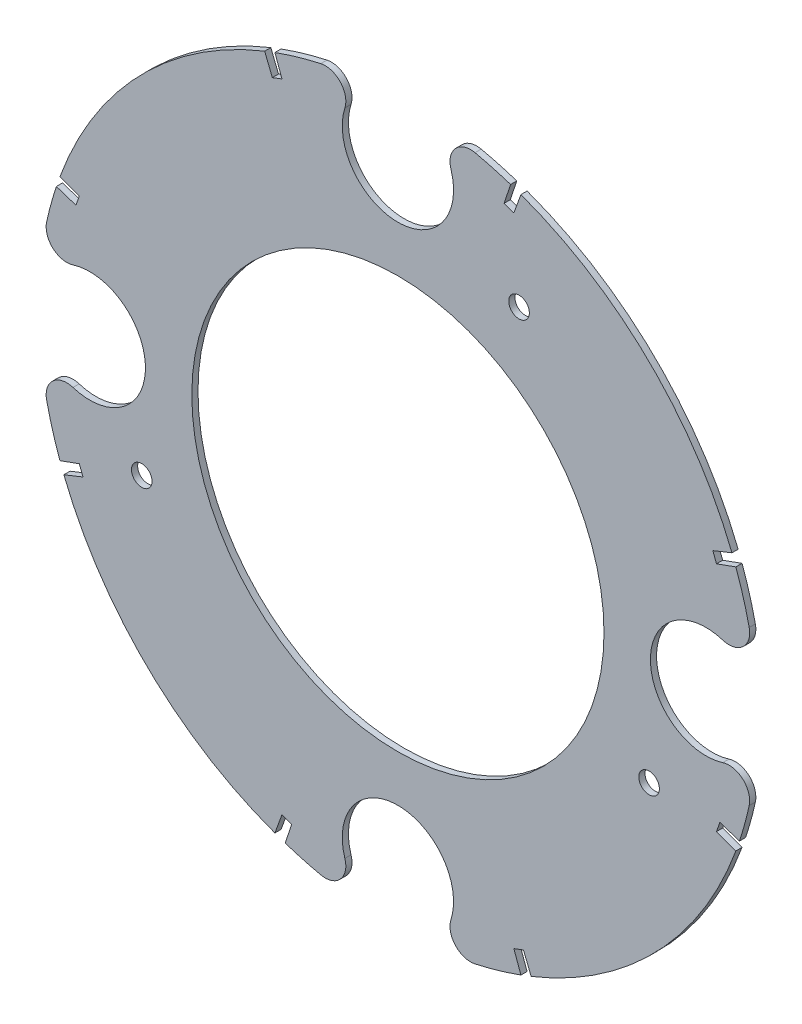
SolidWorks part; units mm, degrees
ref_plane "Front Plane" through (0, 0, 0) normal (0, 0, 1) x (1, 0, 0)
ref_plane "Top Plane" through (0, 0, 0) normal (0, 1, 0) x (1, 0, 0)
ref_plane "Right Plane" through (0, 0, 0) normal (1, 0, 0) x (0, 0, -1)
sketch "Sketch1" plane through (0, 0, 0) normal (0, 0, 1) x (1, 0, 0)
  line L0 (-174.5, 0) -> (-72.12, 0) construction
  line L1 (0, 0) -> (0, -168.1678) construction
  line L14 (-56.2623, -154.5794) -> (-51.5384, -156.2179)
  line L15 (72.12, 0) -> (174.5, 0) construction
  line L16 (-54.6714, -165.7145) -> (-51.5384, -156.2179)
  line L17 (-59.6825, -163.9764) -> (-56.2623, -154.5794)
  line L18 (59.6825, -163.9764) -> (56.2623, -154.5794)
  line L19 (64.6385, -162.0868) -> (60.9342, -152.7981)
  line L20 (56.2623, -154.5794) -> (60.9342, -152.7981)
  line L21 (-163.9764, 59.6825) -> (-154.5794, 56.2623)
  line L22 (-154.5794, 56.2623) -> (-156.2179, 51.5384)
  line L23 (-165.7145, 54.6714) -> (-156.2179, 51.5384)
  line L24 (-163.9764, -59.6825) -> (-154.5794, -56.2623)
  line L25 (-154.5794, -56.2623) -> (-152.7981, -60.9342)
  line L26 (-162.0868, -64.6385) -> (-152.7981, -60.9342)
  line L27 (59.6825, 163.9764) -> (56.2623, 154.5794)
  line L28 (56.2623, 154.5794) -> (51.5384, 156.2179)
  line L29 (54.6714, 165.7145) -> (51.5384, 156.2179)
  line L30 (-59.6825, 163.9764) -> (-56.2623, 154.5794)
  line L31 (-56.2623, 154.5794) -> (-60.9342, 152.7981)
  line L32 (-64.6385, 162.0868) -> (-60.9342, 152.7981)
  line L33 (163.9764, -59.6825) -> (154.5794, -56.2623)
  line L34 (154.5794, -56.2623) -> (156.2179, -51.5384)
  line L35 (165.7145, -54.6714) -> (156.2179, -51.5384)
  line L36 (163.9764, 59.6825) -> (154.5794, 56.2623)
  line L37 (154.5794, 56.2623) -> (152.7981, 60.9342)
  line L38 (162.0868, 64.6385) -> (152.7981, 60.9342)
  arc A5 (-157.6539, -25.7393) -> (-157.6539, 25.7393) centre (-149.5, 0) ccw
  arc A6 (-170.4413, 37.4166) -> (-157.6539, 25.7393) centre (-160.6739, 35.2724) ccw
  arc A7 (-170.4413, -37.4166) -> (-157.6539, -25.7393) centre (-160.6739, -35.2724) cw
  arc A8 (37.4166, 170.4413) -> (25.7393, 157.6539) centre (35.2724, 160.6739) ccw
  arc A9 (-25.7393, 157.6539) -> (25.7393, 157.6539) centre (0, 149.5) ccw
  arc A10 (-37.4166, 170.4413) -> (-25.7393, 157.6539) centre (-35.2724, 160.6739) cw
  arc A11 (170.4413, -37.4166) -> (157.6539, -25.7393) centre (160.6739, -35.2724) ccw
  arc A12 (157.6539, 25.7393) -> (157.6539, -25.7393) centre (149.5, 0) ccw
  arc A13 (170.4413, 37.4166) -> (157.6539, 25.7393) centre (160.6739, 35.2724) cw
  arc A14 (-37.4166, -170.4413) -> (-25.7393, -157.6539) centre (-35.2724, -160.6739) ccw
  arc A15 (25.7393, -157.6539) -> (-25.7393, -157.6539) centre (0, -149.5) ccw
  arc A16 (37.4166, -170.4413) -> (25.7393, -157.6539) centre (35.2724, -160.6739) cw
  circle A30 centre (121.8734, -52.131) radius 5
  circle A31 centre (58.7754, 116.258) radius 5
  circle A32 centre (-124.2895, -46.0393) radius 5
  circle A41 centre (0, 0) radius 100
  arc A42 (-54.6714, -165.7145) -> (-37.4166, -170.4413) centre (0, 0) ccw
  arc A43 (64.6385, -162.0868) -> (163.9764, -59.6825) centre (0, 0) ccw
  arc A44 (-162.0868, -64.6385) -> (-59.6825, -163.9764) centre (0, 0) ccw
  arc A45 (-170.4413, -37.4166) -> (-163.9764, -59.6825) centre (0, 0) ccw
  arc A46 (-37.4166, 170.4413) -> (-59.6825, 163.9764) centre (0, 0) ccw
  arc A47 (170.4413, 37.4166) -> (163.9764, 59.6825) centre (0, 0) ccw
  arc A48 (37.4166, -170.4413) -> (59.6825, -163.9764) centre (0, 0) ccw
  arc A49 (-165.7145, 54.6714) -> (-170.4413, 37.4166) centre (0, 0) ccw
  arc A50 (-64.6385, 162.0868) -> (-163.9764, 59.6825) centre (0, 0) ccw
  arc A51 (54.6714, 165.7145) -> (37.4166, 170.4413) centre (0, 0) ccw
  arc A52 (162.0868, 64.6385) -> (59.6825, 163.9764) centre (0, 0) ccw
  arc A53 (165.7145, -54.6714) -> (170.4413, -37.4166) centre (0, 0) ccw
  point P6 (0, 0)
  point P7 (0, 0)
  point P37 (0, 0)
  point P47 (0, 0)
  point P57 (0, 0)
  point P81 (0, 0)
  point P90 (0, 0)
  dimension "D1" = 25
  dimension "D3" = 4
  dimension "D2" = 27
  dimension "D4" = 200
  dimension "D5" = 174.5
  dimension "D7" = 10
  dimension "D9" = 5
  dimension "D10" = 10
  dimension "D11" = 10
  dimension "D12" = 10
  dimension "D14" = 20
  dimension "D8" = 10
  dimension "D13" = 5
  dimension "D15" = 4
  dimension "D6" = 10
extrude "Boss-Extrude1" add sketch "Sketch1" along normal blind 3
